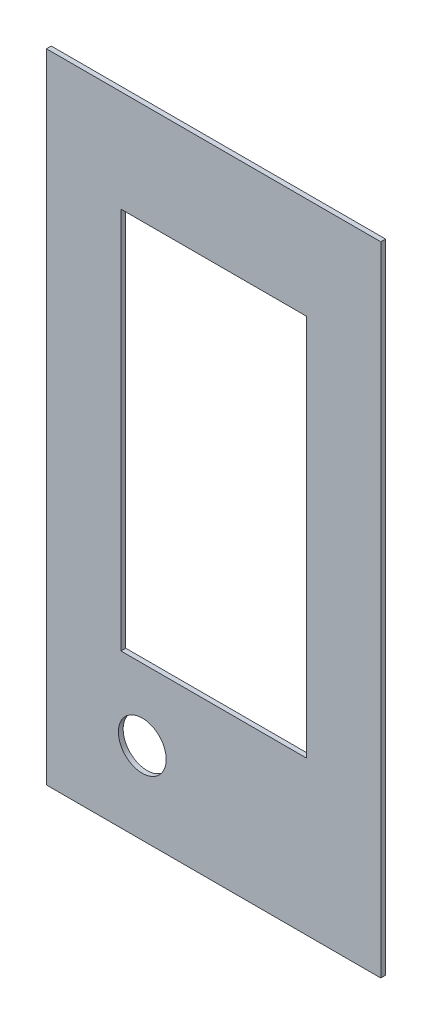
SolidWorks part; units mm, degrees
ref_plane "Спереди" through (0, 0, 0) normal (0, 0, 1) x (1, 0, 0)
ref_plane "Сверху" through (0, 0, 0) normal (0, 1, 0) x (1, 0, 0)
ref_plane "Справа" through (0, 0, 0) normal (1, 0, 0) x (0, 0, -1)
sketch "Эскиз1" plane through (0, 0, 0) normal (0, 1, 0) x (1, 0, 0)
  line L1 (-144.7882, -1.3414) -> (134.7883, -1.3414)
  line L2 (-144.7882, -1.3414) -> (-144.7882, -5.3414)
  line L3 (-144.7882, -5.3414) -> (134.7883, -5.3414)
  line L4 (134.7883, -1.3414) -> (134.7883, -5.3414)
  dimension "D1" = 4
extrude "Вытянуть1" add sketch "Эскиз1" along normal up to surface (533.2137 mm away)
sketch "Эскиз2" plane through (0, 0, 1.3414) normal (0, 0, -1) x (-1, 0, 0)
  circle A0 centre (64.6516, 68.5542) radius 20
extrude "Вырез-Вытянуть1" cut sketch "Эскиз2" against normal through all
sketch "Sketch1" plane through (0, 0, 1.3414) normal (0, 0, -1) x (-1, 0, 0)
  line L0 (-201.6101, 448.2137) -> (228.2599, 448.2137) construction
  line L3 (-351.4591, 128.2137) -> (303.9412, 128.2137) construction
  line L4 (-134.7883, 533.2137) -> (144.7882, 533.2137) construction
  line L5 (5, 533.2137) -> (5, 456.8501) construction
  line L6 (-238.6939, 288.2137) -> (-171.3376, 288.2137) construction
  line L9 (-72.5, 448.2137) -> (82.5, 448.2137)
  line L10 (-72.5, 448.2137) -> (-72.5, 128.2137)
  line L11 (-72.5, 128.2137) -> (82.5, 128.2137)
  line L12 (82.5, 448.2137) -> (82.5, 128.2137)
  line L13 (-72.5, 448.2137) -> (82.5, 128.2137) construction
  line L14 (-72.5, 128.2137) -> (82.5, 448.2137) construction
  point P9 (5, 288.2137)
  dimension "D1" = 320
  dimension "D2" = 85
  dimension "D3" = 160
extrude "Cut-Extrude1" cut sketch "Sketch1" against normal through all contours L10 L11 L12 L9
